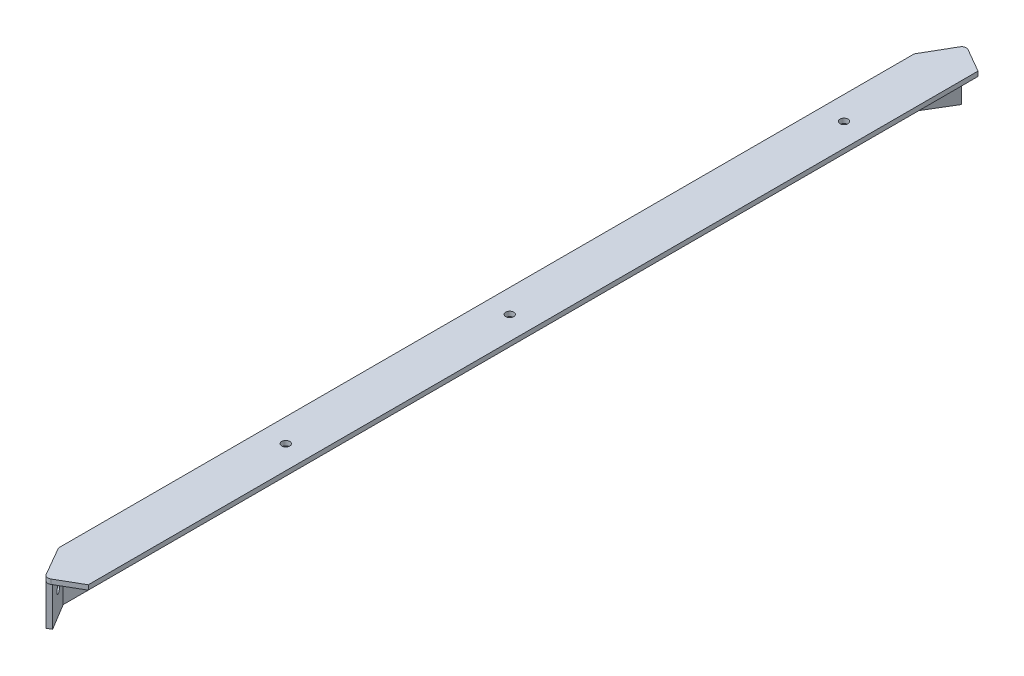
SolidWorks part; units mm, degrees
material "1.0116 (S235J2G3)"
ref_plane "Front Plane" through (0, 0, 0) normal (0, 0, 1) x (1, 0, 0)
ref_plane "Top Plane" through (0, 0, 0) normal (0, 1, 0) x (1, 0, 0)
ref_plane "Right Plane" through (0, 0, 0) normal (1, 0, 0) x (0, 0, -1)
sketch "Sketch1" plane through (0, 0, 0) normal (0, 0, 1) x (1, 0, 0)
  line L6 (0, 0) -> (0, 70)
  line L7 (0, 70) -> (70, 70)
  line L8 (70, 70) -> (70, 63)
  line L9 (70, 63) -> (7, 63)
  line L10 (7, 63) -> (7, 0)
  line L11 (7, 0) -> (0, 0)
  dimension "D1" = 70
  dimension "D2" = 70
  dimension "D3" = 7
  dimension "D4" = 7
extrude "Boss-Extrude1" add sketch "Sketch1" along normal blind 640
sketch "Sketch2" plane through (0, 0, 0) normal (0, 1, 0) x (1, 0, 0)
  line L0 (0, -640) -> (25, -683.3013)
  line L1 (25, -683.3013) -> (31.0622, -679.8013)
  line L2 (31.0622, -679.8013) -> (7, -640)
  line L3 (0, -640) -> (7, -640) construction
  line L4 (7, -640) -> (0, -640)
  line L5 (0, -640) -> (0, 0) construction
  dimension "D1" = 46.5095
  dimension "D2" = 50
  dimension "D3" = 210
  dimension "D4" = 7
extrude "Boss-Extrude2" add sketch "Sketch2" along normal blind 63
sketch "Sketch9" plane through (0, 63, 0) normal (0, 1, 0) x (1, 0, 0)
  line L0 (0, -640) -> (25, -683.3013)
  line L1 (34.5622, -685.8634) -> (70, -665.4034)
  line L2 (70, -665.4034) -> (70, -640)
  line L3 (70, -640) -> (0, -640)
  arc A0 (25, -683.3013) -> (34.5622, -685.8634) centre (31.0622, -679.8013) ccw
  dimension "D5" = 14
  dimension "D2" = 40.9201
  dimension "D1" = 90
  dimension "D3" = 90
  dimension "D4" = 60
  dimension "D6" = 7
  dimension "D7" = 7
extrude "Boss-Extrude4" add sketch "Sketch9" along normal blind 7
sketch "Sketch10" plane through (-278.2276, 0, 168.2047) normal (0.8558, 0, -0.5174) x (-0.5174, 0, -0.8558)
  line L0 (-597.822, 63) -> (-597.822, 0) construction
  line L1 (-597.822, 0) -> (-551.3126, 0) construction
  circle A0 centre (-572.822, 35) radius 6
  dimension "D1" = 12
  dimension "D2" = 25
  dimension "D3" = 35
extrude "Cut-Extrude3" cut sketch "Sketch10" against normal blind 7
sketch "Sketch21" plane through (0, 0, 0) normal (0, 0, -1) x (-1, 0, 0)
  line L0 (0, 70) -> (-70, 70) construction
  line L1 (-70, 70) -> (-70, 0) construction
  line L2 (-70, 0) -> (0, 0) construction
  line L3 (0, 0) -> (0, 69.2595) construction
fillet "Fillet5" radius 5 2 edges at (19.0311, 63, 659.9006) (7, 63, 320)
mirror "Mirror6" about plane through (0, 0, 0) normal (0, 0, 1) of bodies 107 108
sketch "Sketch22" plane through (0, 70, 0) normal (0, 1, 0) x (1, 0, 0)
  line L0 (70, 0) -> (0, 0) construction
  line L1 (0, -38.5) -> (0, 38.5) construction
  circle A0 centre (35, 0) radius 6
  circle A1 centre (35, 500) radius 6
  circle A2 centre (35, -335) radius 6
  dimension "D1" = 12
  dimension "D2" = 12
  dimension "D3" = 12
  dimension "D4" = 500
  dimension "D5" = 335
  dimension "D6" = 35
  dimension "D7" = 35
extrude "Cut-Extrude4" cut sketch "Sketch22" against normal blind 10
